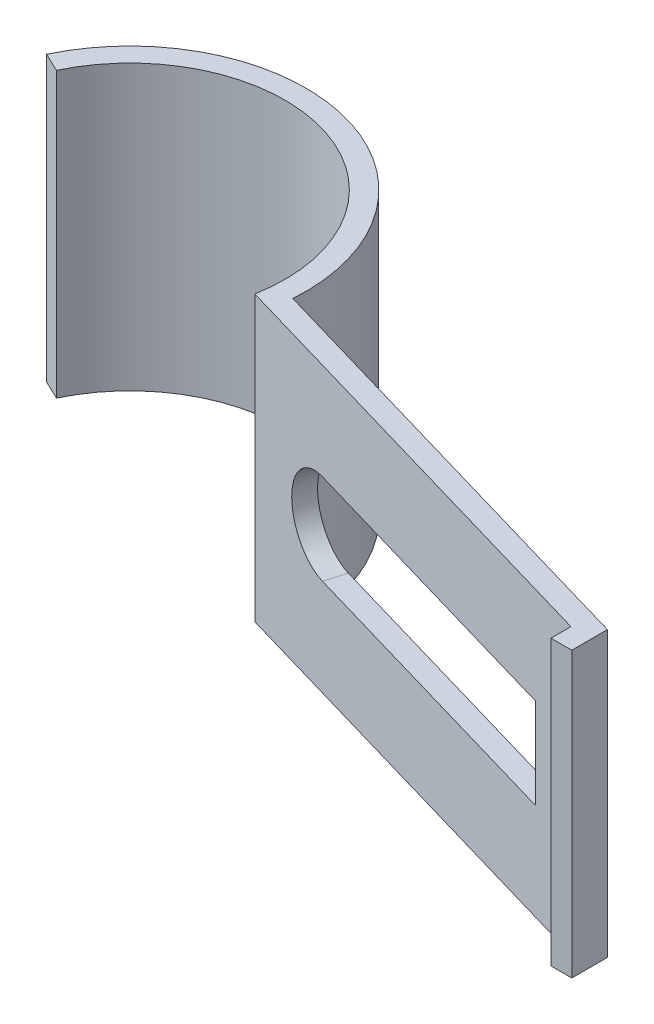
SolidWorks part; units mm, degrees
ref_plane "Front Plane" through (0, 0, 0) normal (0, 0, 1) x (1, 0, 0)
ref_plane "Top Plane" through (0, 0, 0) normal (0, 1, 0) x (1, 0, 0)
ref_plane "Right Plane" through (0, 0, 0) normal (1, 0, 0) x (0, 0, -1)
sketch "Sketch1" plane through (0, 0, 0) normal (0, 1, 0) x (1, 0, 0)
  line L0 (0, 0) -> (0, 0.4) construction
  line L1 (0, 0.4) -> (-6.3939, 2.2637) construction
  line L2 (-4.4506, 0) -> (4.782, 0) construction
  line L3 (-6.3939, 2.2637) -> (-10.9062, 3.5789) construction
  line L4 (-8.65, 2.9213) -> (-8.0904, 4.8414) construction
  line L5 (0.15, 0) -> (0.15, 0.5125)
  line L6 (0.15, 0.5125) -> (-6.2326, 2.3729)
  line L7 (-0.15, 0) -> (-0.15, 0.2875)
  line L8 (-0.15, 0.2875) -> (-6.562, 2.1564)
  line L9 (0.15, 0) -> (-0.15, 0)
  line L10 (-11.0416, 3.6433) -> (-10.7707, 3.5144)
  arc A0 (-6.3939, 2.2637) -> (-10.9062, 3.5789) centre (-8.7566, 2.5558) ccw construction
  arc A1 (-6.2326, 2.3729) -> (-11.0416, 3.6433) centre (-8.7566, 2.5558) ccw
  arc A2 (-6.562, 2.1564) -> (-10.7707, 3.5144) centre (-8.7566, 2.5558) ccw
  point P10 (-8.0904, 4.8414)
  dimension "D1" = 0.4
  dimension "D2" = 6.66
  dimension "D3" = 16.25
  dimension "D4" = 4.7
  dimension "D5" = 2
  dimension "D6" = 0.15
  dimension "D7" = 0.15
extrude "Boss-Extrude1" add sketch "Sketch1" along normal blind 4.08
sketch "Sketch2" plane through (0.1494, 0, -0.5127) normal (0.2798, 0, -0.96) x (-0.96, 0, -0.2798)
  line L0 (-0.0006, 2.04) -> (6.6476, 2.04) construction
  line L1 (-0.0006, 4.08) -> (-0.0006, 0) construction
  line L2 (6.6476, 4.08) -> (6.6476, 0) construction
  line L3 (0.9735, 1.39) -> (0.9735, 2.69)
  line L4 (0.9735, 2.69) -> (5.4735, 2.69)
  line L5 (0.9735, 1.39) -> (5.4735, 1.39)
  arc A0 (5.4735, 2.69) -> (5.4735, 1.39) centre (5.4735, 2.04) cw
  point P13 (0.9735, 2.04)
  dimension "D1" = 1.3
  dimension "D2" = 4.5
  dimension "D3" = 0.9741
extrude "Cut-Extrude1" cut sketch "Sketch2" against normal up to surface (0.3 mm away) up to face at (-3.356, 2.04, -1.2219)
